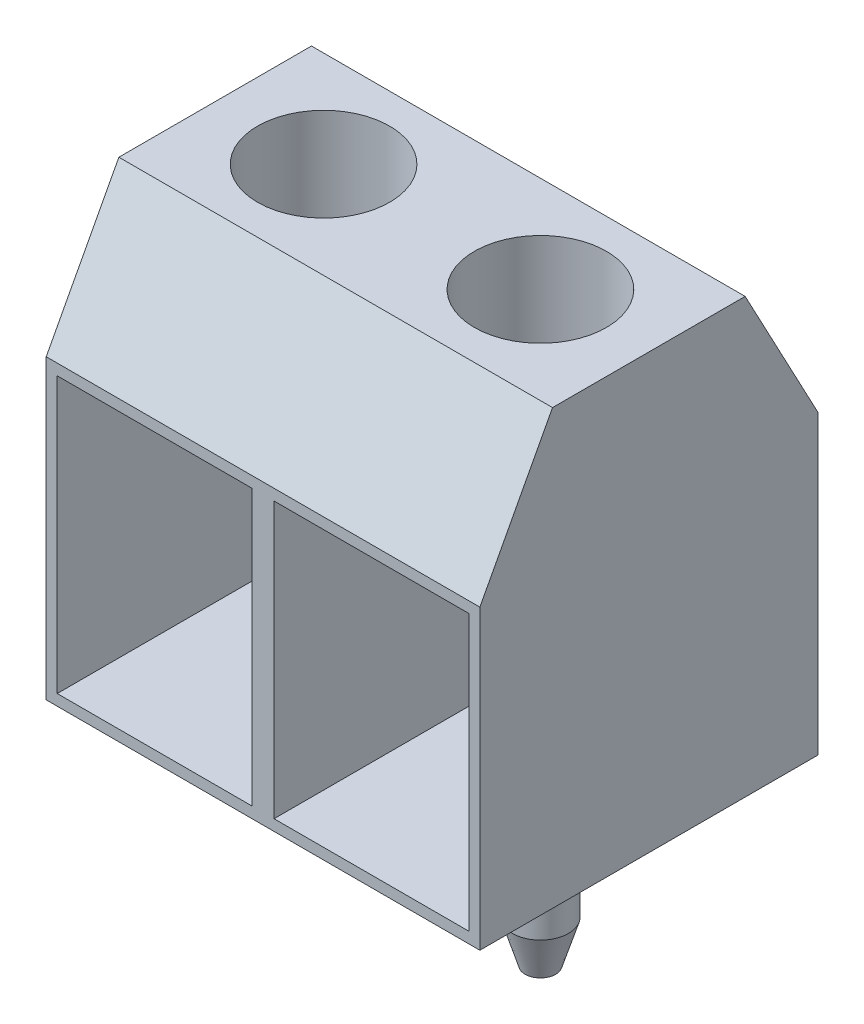
SolidWorks part; units mm, degrees
ref_plane "Front Plane" through (0, 0, 0) normal (0, 0, 1) x (1, 0, 0)
ref_plane "Top Plane" through (0, 0, 0) normal (0, 1, 0) x (1, 0, 0)
ref_plane "Right Plane" through (0, 0, 0) normal (1, 0, 0) x (0, 0, -1)
sketch "Sketch3" plane through (0, 0, 0) normal (0, 1, 0) x (1, 0, 0)
  line L1 (-5.0038, -3.8989) -> (5.0038, -3.8989)
  line L2 (-5.0038, -3.8989) -> (-5.0038, 3.8989)
  line L3 (-5.0038, 3.8989) -> (5.0038, 3.8989)
  line L4 (5.0038, -3.8989) -> (5.0038, 3.8989)
  line L5 (-5.0038, -3.8989) -> (5.0038, 3.8989) construction
  line L6 (-5.0038, 3.8989) -> (5.0038, -3.8989) construction
  point P0 (0, 0)
  dimension "D1" = 7.7978
  dimension "D2" = 10.0076
extrude "Boss-Extrude1" add sketch "Sketch3" along normal blind 10.0076
sketch "Sketch4" plane through (-5.0038, 0, 0) normal (-1, 0, 0) x (0, 0, 1)
  line L0 (-3.8989, 6.858) -> (-2.2225, 10.0076)
  line L1 (2.2225, 10.0076) -> (3.8989, 6.858)
  line L2 (-3.8989, 6.858) -> (3.8989, 6.858) construction
  line L4 (-3.8989, 0) -> (3.8989, 0)
  line L5 (3.8989, 0) -> (3.8989, 10.0076)
  line L6 (3.8989, 10.0076) -> (-3.8989, 10.0076)
  line L7 (-3.8989, 10.0076) -> (-3.8989, 0)
  line L8 (-3.8989, 0) -> (3.8989, 0)
  line L9 (3.8989, 0) -> (3.8989, 6.858)
  line L10 (2.2225, 10.0076) -> (-2.2225, 10.0076)
  line L11 (-3.8989, 6.858) -> (-3.8989, 0)
  line M9 (3.8989, 0) -> (3.8989, 10.0076)
  line M10 (3.8989, 10.0076) -> (-3.8989, 10.0076)
  line M11 (-3.8989, 10.0076) -> (-3.8989, 0)
  dimension "D2" = 6.858
  dimension "D3" = 4.445
  dimension "D1" = 0
extrude "Cut-Extrude1" cut sketch "Sketch4" against normal blind 10.0076 contours L0 M11 M10 | L1 M10 M9
sketch "Sketch5" plane through (0, 10.0076, 0) normal (0, 1, 0) x (1, 0, 0)
  line L0 (0, 0) -> (2.5019, 0) construction
  line L1 (0, 0) -> (-2.5019, 0) construction
  circle A0 centre (-2.5019, 0) radius 1.524
  circle A1 centre (2.5019, 0) radius 1.524
  dimension "D2" = 3.048
  dimension "D1" = 5.0038
extrude "Cut-Extrude2" cut sketch "Sketch5" against normal blind 2.54
sketch "Sketch6" plane through (0, 0, 3.8989) normal (0, 0, 1) x (1, 0, 0)
  line L4 (0, 6.858) -> (0, 0) construction
  line L5 (-0.254, 6.604) -> (-0.254, 0.254)
  line L6 (0.254, 6.604) -> (0.254, 0.254)
  line L7 (-0.254, 6.604) -> (-4.7498, 6.604)
  line L8 (4.7498, 0.254) -> (4.7498, 6.604)
  line L9 (4.7498, 6.604) -> (-4.7498, 6.604)
  line L10 (-4.7498, 6.604) -> (-4.7498, 0.254)
  line L11 (-4.7498, 0.254) -> (4.7498, 0.254)
  line L12 (4.7498, 0.254) -> (4.7498, 6.604)
  line L13 (4.7498, 6.604) -> (0.254, 6.604)
  line L14 (-4.7498, 6.604) -> (-4.7498, 0.254)
  line L15 (-4.7498, 0.254) -> (-0.254, 0.254)
  line L16 (0.254, 0.254) -> (4.7498, 0.254)
  line L17 (0, 6.604) -> (0, 0.254) construction
  line L18 (-5.0038, 0) -> (5.0038, 0) construction
  line L19 (5.0038, 6.858) -> (-5.0038, 6.858) construction
  point P7 (0, 0)
  point P15 (0, 6.858)
  dimension "D1" = 0.254
  dimension "D2" = 0.254
  dimension "D3" = 0.254
extrude "Cut-Extrude3" cut sketch "Sketch6" against normal blind 5.08
sketch "Sketch8" plane through (0, 0, 0) normal (0, -1, 0) x (1, 0, 0)
  circle A0 centre (2.5019, 0) radius 1.524 construction
  circle A1 centre (-2.5019, 0) radius 1.524 construction
  circle A2 centre (2.5019, 0) radius 1.524 construction
  circle A3 centre (-2.5019, 0) radius 1.524 construction
  circle A4 centre (-2.5019, 0) radius 0.6477
  circle A5 centre (2.5019, 0) radius 0.6477
  dimension "D1" = 1.2954
extrude "Boss-Extrude2" add sketch "Sketch8" along normal blind 2.54
sketch "Sketch9" plane through (0, -2.54, 0) normal (0, -1, 0) x (1, 0, 0)
  circle A0 centre (-2.5019, 0) radius 0.6477 construction
  circle A1 centre (2.5019, 0) radius 0.6477
  circle A2 centre (2.5019, 0) radius 0.6477
  circle A3 centre (-2.5019, 0) radius 0.6477
  dimension "D1" = 0
extrude "Boss-Extrude3" add sketch "Sketch9" along normal blind 0.9652 draft 17
